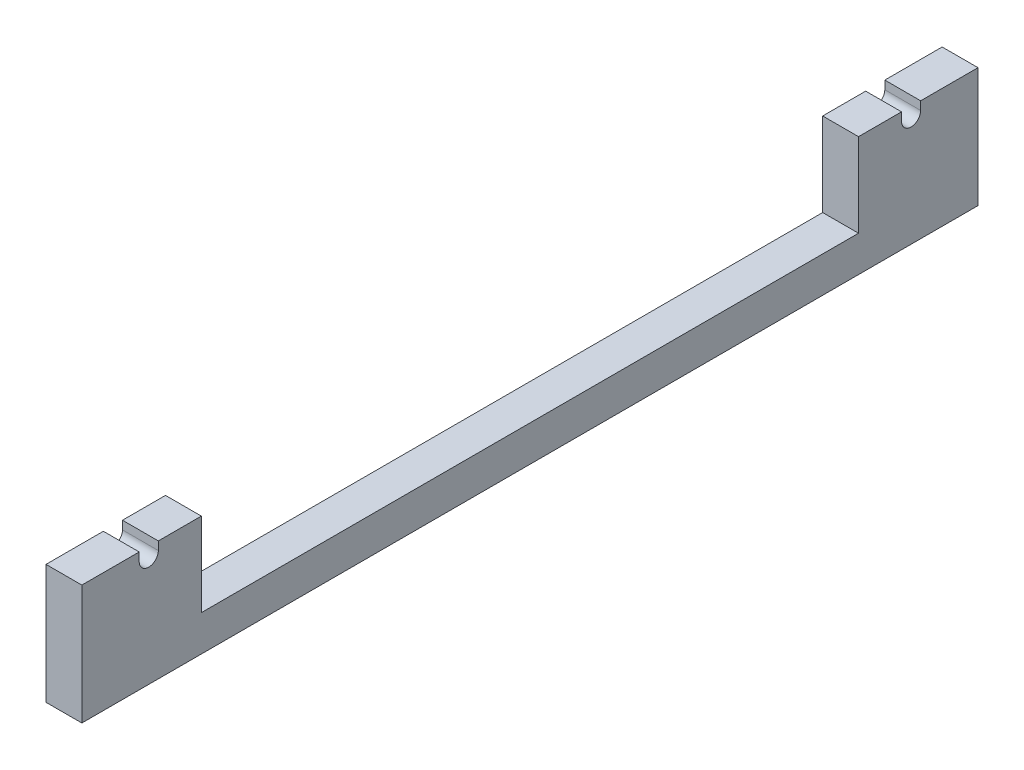
SolidWorks part; units mm, degrees
ref_plane "Alzado" through (0, 0, 0) normal (0, 0, 1) x (1, 0, 0)
ref_plane "Planta" through (0, 0, 0) normal (0, 1, 0) x (1, 0, 0)
ref_plane "Vista lateral" through (0, 0, 0) normal (1, 0, 0) x (0, 0, -1)
sketch "Croquis2" plane through (0, 0, 0) normal (1, 0, 0) x (0, 0, -1)
  line L0 (0, 0) -> (375, 0)
  line L1 (375, 0) -> (375, 50)
  line L2 (375, 50) -> (351, 50)
  line L3 (325, 50) -> (325, 15)
  line L4 (325, 15) -> (50, 15)
  line L5 (50, 15) -> (50, 50)
  line L6 (50, 50) -> (32, 50)
  line L7 (0, 50) -> (0, 0)
  line L8 (24, 50) -> (0, 50)
  line L9 (24, 46.5) -> (24, 50)
  line L10 (32, 46.5) -> (32, 50)
  line L11 (343, 46.5) -> (343, 50)
  line L12 (351, 46.5) -> (351, 50)
  line L13 (343, 50) -> (325, 50)
  arc A0 (24, 46.5) -> (32, 46.5) centre (28, 46.5) ccw
  arc A1 (343, 46.5) -> (351, 46.5) centre (347, 46.5) ccw
  dimension "D6" = 8
  dimension "D1" = 375
  dimension "D2" = 15
  dimension "D3" = 50
  dimension "D4" = 50
  dimension "D5" = 28
  dimension "D7" = 46.5
  dimension "D8" = 50
  dimension "D9" = 28
extrude "Saliente-Extruir3" add sketch "Croquis2" along normal blind 15
